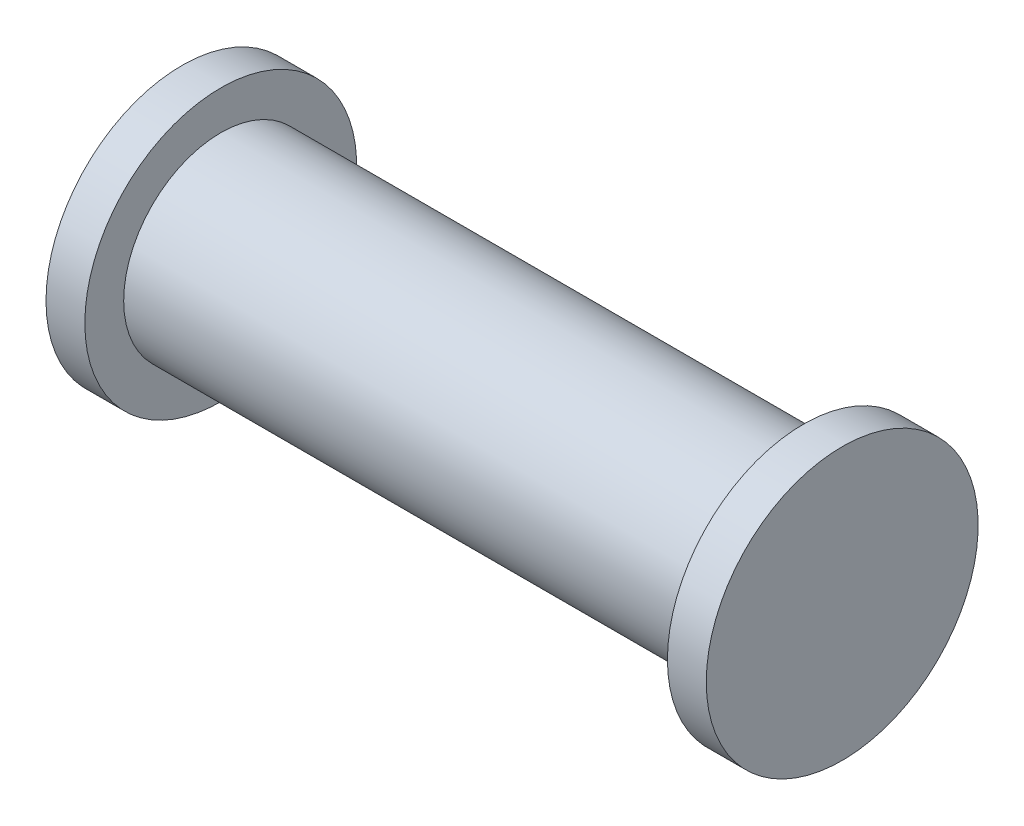
SolidWorks part; units mm, degrees
material "6061 Alloy"
ref_plane "Front Plane" through (0, 0, 0) normal (0, 0, 1) x (1, 0, 0)
ref_plane "Top Plane" through (0, 0, 0) normal (0, 1, 0) x (1, 0, 0)
ref_plane "Right Plane" through (0, 0, 0) normal (1, 0, 0) x (0, 0, -1)
sketch "Sketch1" plane through (0, 0, 0) normal (0, 0, 1) x (1, 0, 0)
  line L0 (0, 0) -> (0, 5) construction
  line L1 (-15, 5) -> (15, 5)
  line L2 (-15, 5) -> (-15, 7)
  line L3 (-15, 7) -> (-17, 7)
  line L4 (-17, 7) -> (-17, 0)
  line L5 (-17, 0) -> (17, 0)
  line L6 (17, 0) -> (17, 7)
  line L7 (17, 7) -> (15, 7)
  line L8 (15, 7) -> (15, 5)
  point P5 (0, 5)
  dimension "D1" = 5
  dimension "D2" = 30
  dimension "D3" = 2
  dimension "D4" = 2
  dimension "D5" = 7
  dimension "D6" = 2
revolve "Revolve1" add sketch "Sketch1" angle 360 about L5
